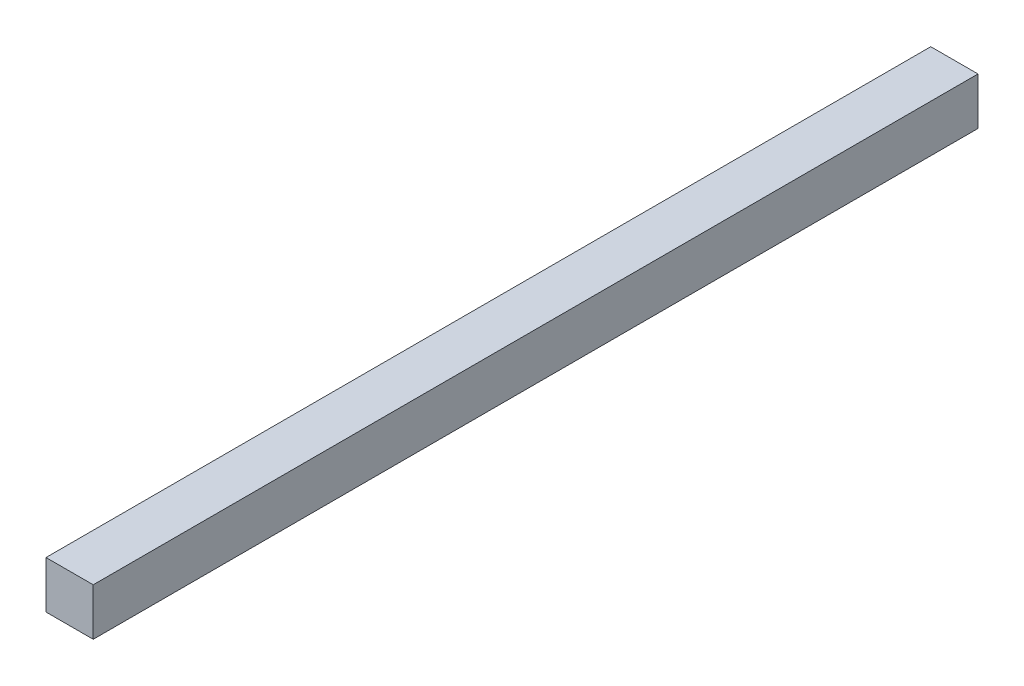
SolidWorks part; units mm, degrees
ref_plane "前视基准面" through (0, 0, 0) normal (0, 0, 1) x (1, 0, 0)
ref_plane "上视基准面" through (0, 0, 0) normal (0, 1, 0) x (1, 0, 0)
ref_plane "右视基准面" through (0, 0, 0) normal (1, 0, 0) x (0, 0, -1)
sketch "草图1" plane through (0, 0, 0) normal (0, 0, 1) x (1, 0, 0)
  line L1 (-15, 15) -> (15, 15)
  line L2 (-15, 15) -> (-15, -15)
  line L3 (-15, -15) -> (15, -15)
  line L4 (15, 15) -> (15, -15)
  line L5 (0, -15) -> (0, 15) construction
  line L6 (-15, 0) -> (15, 0) construction
  point P0 (0, 0)
  dimension "D1" = 30
extrude "凸台-拉伸1" add sketch "草图1" along normal mid plane 562
